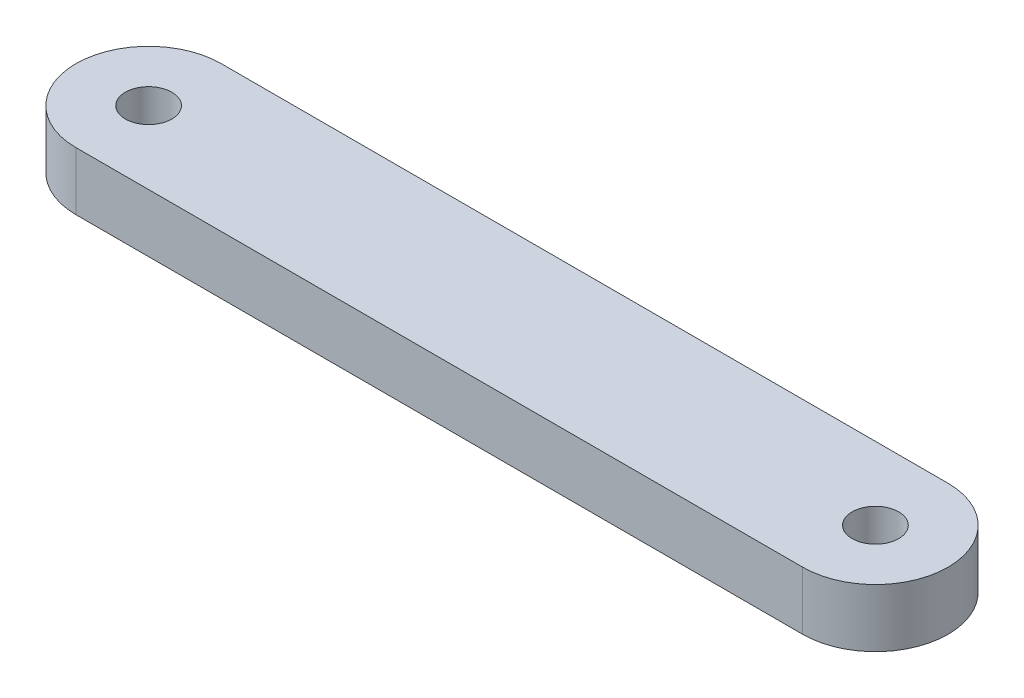
SolidWorks part; units mm, degrees
ref_plane "正面" through (0, 0, 0) normal (0, 0, 1) x (1, 0, 0)
ref_plane "平面" through (0, 0, 0) normal (0, 1, 0) x (1, 0, 0)
ref_plane "右側面" through (0, 0, 0) normal (1, 0, 0) x (0, 0, -1)
sketch "ｽｹｯﾁ1" plane through (0, 0, 0) normal (0, 1, 0) x (1, 0, 0)
  line L0 (0, 0) -> (110, 0) construction
  line L1 (0, -5) -> (50, -5)
  line L3 (0, 5) -> (50, 5)
  circle A0 centre (0, 0) radius 1.6
  circle A1 centre (50, 0) radius 1.6
  arc A2 (0, 5) -> (0, -5) centre (0, 0) ccw
  arc A3 (50, -5) -> (50, 5) centre (50, 0) ccw
  dimension "D5" = 3.2
  dimension "D1" = 5
  dimension "D2" = 5
  dimension "D4" = 50
extrude "ﾎﾞｽ - 押し出し1" add sketch "ｽｹｯﾁ1" along normal blind 4
